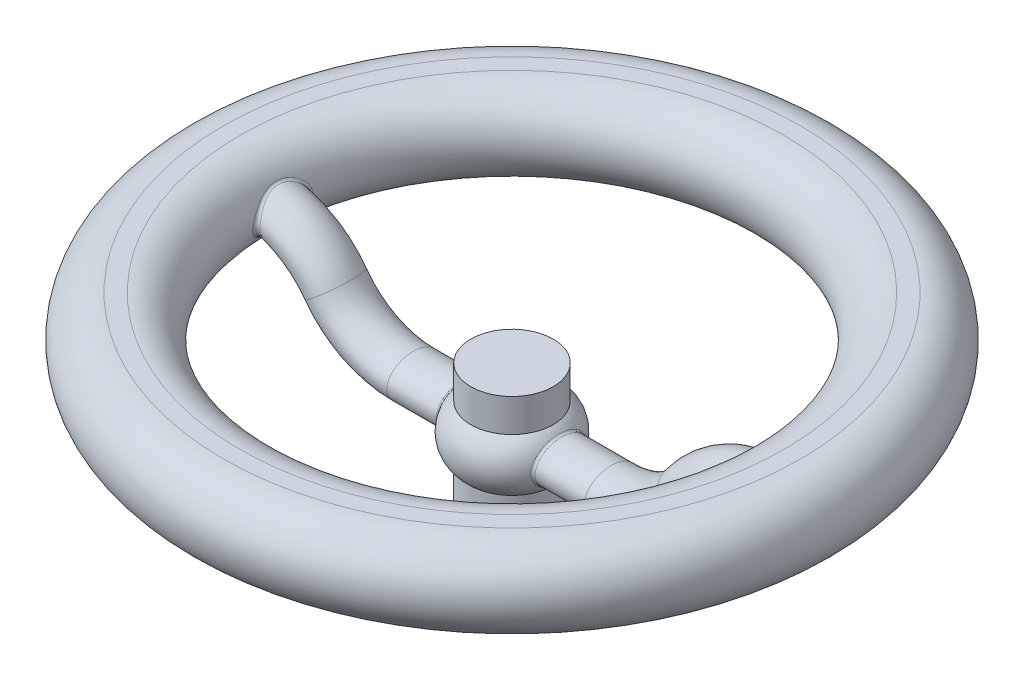
SolidWorks part; units mm, degrees
material "Сталь"
ref_plane "Спереди" through (0, 0, 0) normal (0, 0, 1) x (1, 0, 0)
ref_plane "Сверху" through (0, 0, 0) normal (0, 1, 0) x (1, 0, 0)
ref_plane "Справа" through (0, 0, 0) normal (1, 0, 0) x (0, 0, -1)
sketch "Эскиз1" plane through (0, 0, 0) normal (0, 0, 1) x (1, 0, 0)
  line L0 (-12.5, 35) -> (-12.5, 45)
  line L1 (0, 0) -> (-12.5, 0)
  line L2 (0, 0) -> (0, 45) construction
  line L3 (0, 45) -> (-12.5, 45)
  line L4 (-12.5, 0) -> (-12.5, 19)
  line L5 (0, 0) -> (0, 45)
  arc A0 (-12.5, 35) -> (-12.5, 19) centre (-6.5, 27) ccw
  dimension "D4" = 4
  dimension "D1" = 25
  dimension "D2" = 45
  dimension "D3" = 16
  dimension "D5" = 10
revolve "Повернуть1" add sketch "Эскиз1" angle 360 about L2
sketch "Эскиз2" plane through (0, 0, 0) normal (0, 0, 1) x (1, 0, 0)
  line L0 (-87.5, 51) -> (-82.5, 51) construction
  line L1 (-87.5, 63.5) -> (-82.5, 63.5)
  line L2 (-87.5, 38.5) -> (-82.5, 38.5)
  line L3 (0, 0) -> (0, 105.4539) construction
  line L4 (12.5, 45) -> (-12.5, 45) construction
  arc A0 (-87.5, 63.5) -> (-87.5, 38.5) centre (-87.5, 51) ccw
  arc A1 (-82.5, 38.5) -> (-82.5, 63.5) centre (-82.5, 51) ccw
  point P2 (-85, 51)
  dimension "D4" = 30
  dimension "D1" = 170
  dimension "D2" = 6
  dimension "D3" = 25
revolve "Повернуть2" add sketch "Эскиз2" angle 360 about L3
sketch "Эскиз3" plane through (0, 0, 0) normal (0, 0, 1) x (1, 0, 0)
  line L0 (0, 0) -> (0, 70.0258) construction
  line L1 (-12.5, 0) -> (12.5, 0) construction
  line L2 (0, 27) -> (-30, 27)
  line L3 (-70, 51) -> (-100, 51) construction
  line L4 (-85, 51) -> (-85, 63.5027) construction
  line L5 (-76.9894, 51) -> (-85, 51)
  line L6 (-16.5, 27) -> (16.5, 27) construction
  arc A0 (-30, 27) -> (-53.4947, 39) centre (-30, 56) cw
  arc A1 (-53.4947, 39) -> (-76.9894, 51) centre (-76.9894, 22) ccw
  arc A4 (-82.5, 38.5) -> (-82.5, 63.5) centre (-82.5, 51) ccw construction
  arc A5 (-87.5, 63.5) -> (-87.5, 38.5) centre (-87.5, 51) ccw construction
  arc A6 (-12.5, 35) -> (-12.5, 19) centre (-6.5, 27) ccw construction
  arc A7 (12.5, 19) -> (12.5, 35) centre (6.5, 27) ccw construction
  point P28 (0, 0)
  dimension "D1" = 29
  dimension "D2" = 55
sketch "Эскиз4" plane through (0, 0, 0) normal (1, 0, 0) x (0, 0, -1)
  line L0 (0, 39) -> (0, 27) construction
  line L1 (0, 0) -> (0, 70.0258) construction
  line L2 (-16.5, 27) -> (16.5, 27) construction
  arc A0 (-12.5, 35) -> (-12.5, 19) centre (-6.5, 27) ccw construction
  arc A1 (12.5, 19) -> (12.5, 35) centre (6.5, 27) ccw construction
  ellipse E0 centre (0, 27) end of major axis (8, 27) minor radius 6
  dimension "D1" = 12
  dimension "D2" = 16
sweep "По траектории1" add profiles "Эскиз4" path "Эскиз3"
fillet "Скругление1" radius 1 2 edges at (-14.4353, 25.9951, 7.887) (-69.5685, 50.1839, 7.9977)
pattern_circular "Круговой массив1" count 2 over 360 about axis through (0, 0, 0) along (0, -1, 0) of "По траектории1", "Скругление1"
